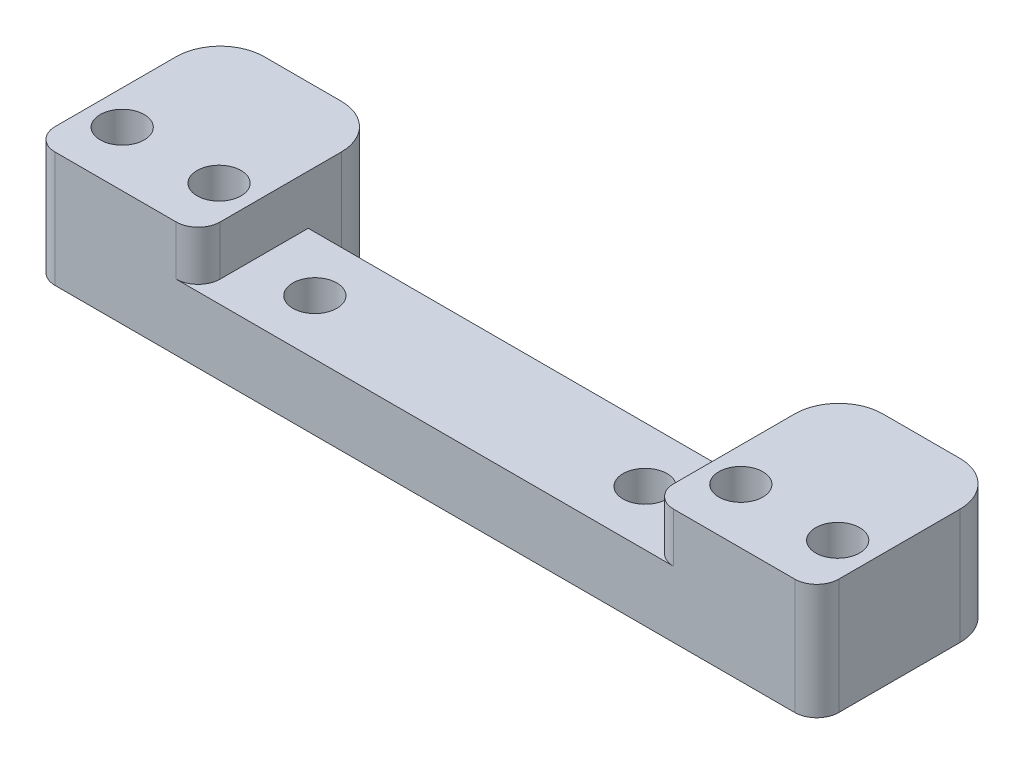
SolidWorks part; units mm, degrees
ref_plane "Front Plane" through (0, 0, 0) normal (0, 0, 1) x (1, 0, 0)
ref_plane "Top Plane" through (0, 0, 0) normal (0, 1, 0) x (1, 0, 0)
ref_plane "Right Plane" through (0, 0, 0) normal (1, 0, 0) x (0, 0, -1)
sketch "Sketch1" plane through (0, 0, 0) normal (0, 1, 0) x (1, 0, 0)
  line L0 (-32.5, 0) -> (-23.7, 0) construction
  line L5 (-23.7, 0) -> (23.7, 0) construction
  line L6 (23.7, 0) -> (32.5, 0) construction
  line L7 (-35.6, 5) -> (35.6, 5)
  line L14 (-15, 0) -> (0, 5.3489) construction
  line L15 (0, 5.3489) -> (15, 0) construction
  line L16 (-35.6, -5) -> (35.6, -5)
  line L17 (0, 5) -> (0, 0) construction
  line L18 (0, 0) -> (0, -5) construction
  line L19 (-35.6, 5) -> (-35.6, -5)
  line L20 (35.6, 5) -> (35.6, -5)
  circle A0 centre (-32.5, 0) radius 2
  circle A1 centre (-23.7, 0) radius 2
  circle A2 centre (23.7, 0) radius 2
  circle A3 centre (32.5, 0) radius 2
  circle A6 centre (-15, 0) radius 2
  circle A7 centre (15, 0) radius 2
  point P22 (-28.1, 0)
  dimension "D1" = 4
  dimension "D3" = 8.7
  dimension "D5" = 30
  dimension "D2" = 8.8
  dimension "D4" = 10
  dimension "D6" = 7.5
extrude "Boss-Extrude1" add sketch "Sketch1" along normal blind 6
sketch "Sketch6" plane through (0, 6, 0) normal (0, 1, 0) x (1, 0, 0)
  line L1 (-35.6, -5) -> (-20.6, -5)
  line L2 (-35.6, -5) -> (-35.6, 12)
  line L3 (-35.6, 12) -> (-20.6, 12)
  line L4 (-20.6, -5) -> (-20.6, 12)
  line L5 (35.6, -5) -> (20.6, -5)
  line L6 (35.6, -5) -> (35.6, 12)
  line L7 (35.6, 12) -> (20.6, 12)
  line L8 (20.6, -5) -> (20.6, 12)
  circle A0 centre (-23.7, 0) radius 2 construction
  circle A1 centre (32.5, 0) radius 2 construction
  circle A2 centre (23.7, 0) radius 2 construction
  circle A3 centre (-32.5, 0) radius 2 construction
  circle A4 centre (32.5, 0) radius 2
  circle A5 centre (23.7, 0) radius 2
  circle A6 centre (-23.7, 0) radius 2
  circle A7 centre (-32.5, 0) radius 2
  dimension "D1" = 15
  dimension "D2" = 12
extrude "Boss-Extrude5" add sketch "Sketch6" against normal up to surface (6 mm away) up to face at (0, 0, 0)
fillet "Fillet1" radius 4 4 edges at (35.6, 3, -12) (20.6, 3, -12) (-35.6, 3, -12) (-20.6, 3, -12)
sketch "Sketch7" plane through (0, 6, 0) normal (0, 1, 0) x (1, 0, 0)
  line L0 (31.6, 12) -> (24.6, 12) construction
  line L1 (-24.6, 12) -> (-31.6, 12) construction
  line L2 (31.6, 12) -> (24.6, 12)
  line L3 (-24.6, 12) -> (-31.6, 12)
  line L4 (-35.6, 8) -> (-35.6, -5)
  line L5 (-35.6, -5) -> (-20.6, -5)
  line L6 (-35.6, -5) -> (35.6, -5) construction
  line L7 (-20.6, -5) -> (-20.6, 8)
  line L8 (20.6, 8) -> (20.6, -5)
  line L9 (20.6, -5) -> (35.6, -5)
  line L10 (35.6, -5) -> (35.6, 8)
  arc A0 (35.6, 8) -> (31.6, 12) centre (31.6, 8) ccw construction
  arc A1 (24.6, 12) -> (20.6, 8) centre (24.6, 8) ccw construction
  arc A2 (-20.6, 8) -> (-24.6, 12) centre (-24.6, 8) ccw construction
  arc A3 (-31.6, 12) -> (-35.6, 8) centre (-31.6, 8) ccw construction
  arc A4 (35.6, 8) -> (31.6, 12) centre (31.6, 8) ccw
  arc A5 (24.6, 12) -> (20.6, 8) centre (24.6, 8) ccw
  arc A6 (-20.6, 8) -> (-24.6, 12) centre (-24.6, 8) ccw
  arc A7 (-31.6, 12) -> (-35.6, 8) centre (-31.6, 8) ccw
  circle A8 centre (32.5, 0) radius 2 construction
  circle A9 centre (23.7, 0) radius 2 construction
  circle A10 centre (-23.7, 0) radius 2 construction
  circle A11 centre (-32.5, 0) radius 2 construction
  circle A12 centre (32.5, 0) radius 2
  circle A13 centre (23.7, 0) radius 2
  circle A14 centre (-23.7, 0) radius 2
  circle A15 centre (-32.5, 0) radius 2
extrude "Boss-Extrude6" add sketch "Sketch7" along normal blind 4.5
fillet "Fillet2" radius 2 4 edges at (35.6, 5.25, 5) (20.6, 8.25, 5) (-35.6, 5.25, 5) (-20.6, 8.25, 5)
